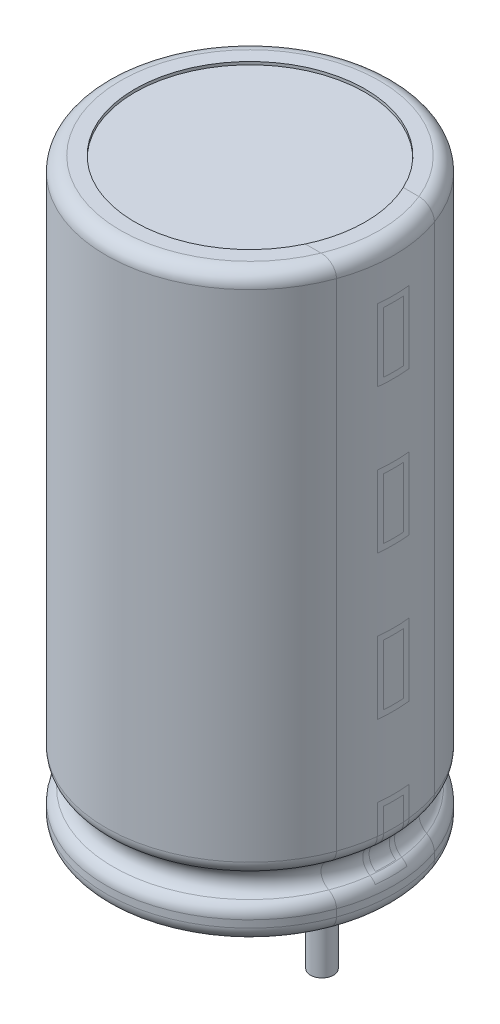
SolidWorks part; units mm, degrees
ref_plane "Front Plane" through (0, 0, 0) normal (0, 0, 1) x (1, 0, 0)
ref_plane "Top Plane" through (0, 0, 0) normal (0, 1, 0) x (1, 0, 0)
ref_plane "Right Plane" through (0, 0, 0) normal (1, 0, 0) x (0, 0, -1)
sketch "Sketch1" plane through (0, 0, 0) normal (0, 1, 0) x (1, 0, 0)
  line L0 (-2.5, 0) -> (2.5, 0) construction
  circle A0 centre (-2.5, 0) radius 0.4
  circle A1 centre (2.5, 0) radius 0.4
  dimension "D3" = 0.8
  dimension "D1" = 5
extrude "Boss-Extrude1" add sketch "Sketch1" against normal blind 3 and the other way blind 1
sketch "Sketch3" plane through (0, 0, 0) normal (0, 0, 1) x (1, 0, 0)
  line L1 (0, 0.1) -> (0, 20.2) construction
  line L2 (5, 0.5) -> (5, 0.75)
  line L3 (0, 0.1) -> (4, 0.1)
  line L4 (4, 20.2) -> (4.5, 20.2)
  line L5 (4, 0) -> (4.5, 0)
  line L6 (0, 20.1) -> (4, 20.1)
  line L7 (5, 2.4821) -> (5, 19.7)
  line L8 (4, 20.1) -> (4, 20.2)
  line L9 (5, 2.4821) -> (5, 20.2) construction
  line L10 (4, 0) -> (4, 0.1)
  line L11 (0, 20.1) -> (5, 20.1) construction
  line L12 (0, 20.2) -> (5, 20.2) construction
  line L13 (4, 2.4821) -> (4, 20.2) construction
  line L14 (0, 0.1) -> (0, 20.1)
  line L17 (0, 0.1) -> (5, 0.1) construction
  line L18 (0, 0) -> (5, 0) construction
  arc A0 (4.75, 2.049) -> (4.75, 1.183) centre (5, 1.616) ccw
  arc A1 (5, 0.75) -> (4.75, 1.183) centre (4.5, 0.75) ccw
  arc A2 (5, 2.4821) -> (4.75, 2.049) centre (4.5, 2.4821) cw
  arc A3 (5, 19.7) -> (4.5, 20.2) centre (4.5, 19.7) ccw
  arc A4 (4.5, 0) -> (5, 0.5) centre (4.5, 0.5) ccw
  point P1 (0, 0)
  point P2 (0, 20.2)
  point P13 (5, 2.116)
  point P29 (0, 0)
  point P32 (4.5, 1.616)
  dimension "D2" = 0.5
  dimension "D1" = 0.5
  dimension "D3" = 20
  dimension "D6" = 1
  dimension "D7" = 0.1
  dimension "D10" = 0.25
  dimension "D11" = 8
  dimension "D4" = 10
  dimension "D12" = 9
  dimension "D5" = 1
revolve "Revolve1" add sketch "Sketch3" angle 360 about L14
sketch "Sketch4" plane through (0, 0, 0) normal (1, 0, 0) x (0, 0, -1)
  line L0 (-4.5, 0) -> (4.5, 0) construction
  line L1 (-1.7, 0) -> (1.7, 0)
  line L2 (0, 0) -> (0, 20.2) construction
  line L3 (-1.7, 20.2) -> (1.7, 20.2)
  line L4 (1.7, 0) -> (1.7, 20.2)
  line L5 (4, 20.2) -> (-4, 20.2) construction
  line L6 (-1.7, 0) -> (-1.7, 20.2)
  line L7 (-0.35, 13.3) -> (-0.35, 11.2)
  line L8 (-0.35, 13.3) -> (0.35, 13.3)
  line L9 (0, 13.3) -> (0, 11.2) construction
  line L10 (-0.35, 11.2) -> (0.35, 11.2)
  line L11 (0.35, 13.3) -> (0.35, 11.2)
  line L12 (0.55, 13.5) -> (0.55, 11)
  line L13 (-0.55, 11) -> (0.55, 11)
  line L14 (-0.55, 13.5) -> (-0.55, 11)
  line L15 (-0.55, 13.5) -> (0.55, 13.5)
  line L16 (0, 0) -> (0, -3.7489) construction
  line L17 (-0.35, 8.3) -> (-0.35, 6.2)
  line L18 (-0.35, 8.3) -> (0.35, 8.3)
  line L19 (-0.35, 6.2) -> (0.35, 6.2)
  line L20 (0.35, 8.3) -> (0.35, 6.2)
  line L21 (0.55, 8.5) -> (0.55, 6)
  line L22 (-0.55, 6) -> (0.55, 6)
  line L23 (-0.55, 8.5) -> (-0.55, 6)
  line L24 (-0.55, 8.5) -> (0.55, 8.5)
  line L25 (0, 8.3) -> (0, 6.2) construction
  line L26 (-0.35, 3.3) -> (-0.35, 1.2)
  line L27 (-0.35, 3.3) -> (0.35, 3.3)
  line L28 (-0.35, 1.2) -> (0.35, 1.2)
  line L29 (0.35, 3.3) -> (0.35, 1.2)
  line L30 (0.55, 3.5) -> (0.55, 1)
  line L31 (-0.55, 1) -> (0.55, 1)
  line L32 (-0.55, 3.5) -> (-0.55, 1)
  line L33 (-0.55, 3.5) -> (0.55, 3.5)
  line L34 (0, 3.3) -> (0, 1.2) construction
  line L35 (-0.55, 18.5) -> (0.55, 18.5)
  line L36 (-0.55, 18.5) -> (-0.55, 16)
  line L37 (-0.35, 18.3) -> (0.35, 18.3)
  line L38 (0.35, 18.3) -> (0.35, 16.2)
  line L39 (0.55, 18.5) -> (0.55, 16)
  line L40 (-0.35, 18.3) -> (-0.35, 16.2)
  line L41 (-0.35, 16.2) -> (0.35, 16.2)
  line L42 (-0.55, 16) -> (0.55, 16)
  line L51 (-0.55, 11) -> (-0.55, 8.5) construction
  line L52 (-0.55, 13.5) -> (-0.55, 16) construction
  point P64 (0, 18.3)
  dimension "D5" = 3.4
  dimension "D6" = 0.2
  dimension "D7" = 1.1
  dimension "D8" = 2.1
  dimension "D1" = 0.7
  dimension "D9" = 1
  dimension "D10" = 2.5
  dimension "D2" = 3
  dimension "D3" = 2
split line "Split Line1"
